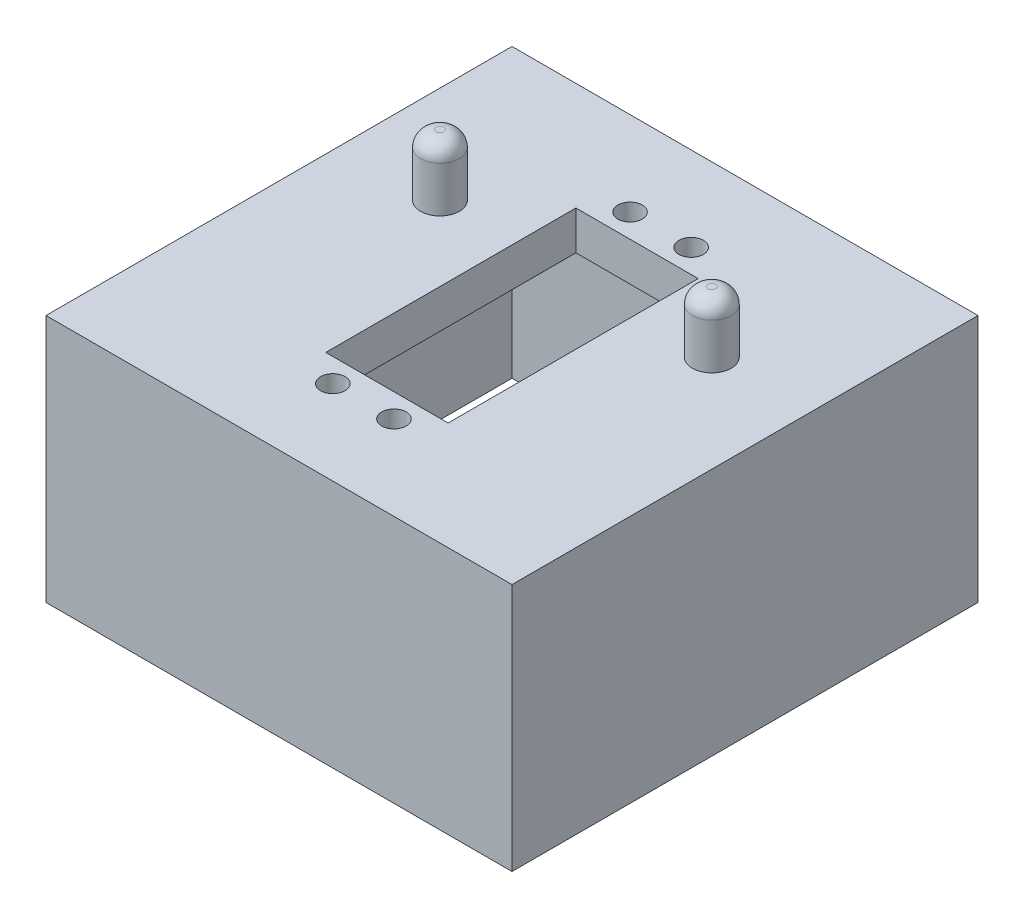
SolidWorks part; units mm, degrees
ref_plane "Front Plane" through (0, 0, 0) normal (0, 0, 1) x (1, 0, 0)
ref_plane "Top Plane" through (0, 0, 0) normal (0, 1, 0) x (1, 0, 0)
ref_plane "Right Plane" through (0, 0, 0) normal (1, 0, 0) x (0, 0, -1)
sketch "Sketch1" plane through (0, 0, 0) normal (0, 0, 1) x (1, 0, 0)
  line L1 (11.3, 0) -> (64.9, 0)
  line L2 (11.3, 0) -> (11.3, 40.64)
  line L3 (11.3, 40.64) -> (64.9, 40.64)
  line L4 (64.9, 0) -> (64.9, 40.64)
  line L5 (0, 0) -> (76.2, 0)
  line L6 (0, 0) -> (0, 40.64)
  line L7 (0, 40.64) -> (76.2, 40.64)
  line L8 (76.2, 0) -> (76.2, 40.64)
  point P11 (38.1, 0)
  point P12 (38.1, 0)
  dimension "D1" = 40.64
  dimension "D2" = 53.6
  dimension "D3" = 76.2
extrude "Boss-Extrude1" add sketch "Sketch1" along normal blind 76.2 contours L1 L4 L3 L2 | L7 L6 L5 L2 | L5 L8 L7 L4
shell "Shell1" thickness 6.35
sketch "Sketch2" plane through (0, 40.64, 0) normal (0, 1, 0) x (1, 0, 0)
  line L1 (0, -76.2) -> (0, 0) construction
  line L3 (0, -76.2) -> (76.2, -76.2) construction
  point P11 (0, -38.1)
  point P12 (33.1, -38.1)
  point P14 (38.1, -76.2)
  point P15 (38.1, -13.8)
  point P20 (38.1, -58.55)
  point P21 (28.1, -38.1)
  line B0 (33.1, -13.8) -> (33.1, -62.4) construction
  line B1 (33.1, -13.8) -> (43.1, -13.8) construction
  line B2 (28.1, -58.55) -> (48.1, -58.55)
  line B3 (28.1, -58.55) -> (28.1, -17.65)
  line B4 (28.1, -17.65) -> (48.1, -17.65)
  line B5 (48.1, -58.55) -> (48.1, -17.65)
  circle B6 centre (33.1, -13.8) radius 2
  circle B7 centre (43.1, -13.8) radius 2
  circle B8 centre (33.1, -62.4) radius 2
  circle B9 centre (43.1, -62.4) radius 2
sketch_block_instance "Block1-1"
sketch_block "Block1" parameters "D1"=4, "D2"=10, "D3"=48.6, "D4"=40.9, "D5"=20
extrude "Cut-Extrude1" cut sketch "Sketch2" against normal through all contours B2 B5 B4 B3 | B9 | B8 | B6 | B7
sketch "Sketch3" plane through (0, 40.64, 0) normal (0, 1, 0) x (1, 0, 0)
  line L0 (15.875, -27.6504) -> (60.325, -27.6504) construction
  line L1 (0, -76.2) -> (76.2, -76.2) construction
  line L3 (0, 0) -> (76.2, 0) construction
  circle A0 centre (15.875, -27.6504) radius 3.175
  circle A1 centre (60.325, -27.6504) radius 3.175
  point P6 (38.1, -76.2)
  point P7 (38.1, -27.6504)
  dimension "D1" = 6.35
  dimension "D2" = 44.45
  dimension "D3" = 27.6504
extrude "Boss-Extrude2" add sketch "Sketch3" along normal blind 10
fillet "Fillet2" radius 2.54 2 edges at (15.875, 50.64, 30.8254) (60.325, 50.64, 30.8254)
sketch "Sketch5" plane through (0, 0, 0) normal (0, 0, -1) x (-1, 0, 0)
  line L0 (0, 0) -> (-76.2, 0) construction
  line L1 (-44.45, 0) -> (-31.75, 0)
  line L2 (-44.45, 0) -> (-44.45, 6.35)
  line L3 (-44.45, 6.35) -> (-31.75, 6.35)
  line L4 (-31.75, 0) -> (-31.75, 6.35)
  line L5 (0, 40.64) -> (-76.2, 40.64) construction
  point P8 (-38.1, 40.64)
  point P9 (-38.1, 6.35)
  dimension "D1" = 6.35
  dimension "D2" = 12.7
extrude "Cut-Extrude2" cut sketch "Sketch5" against normal up to next
